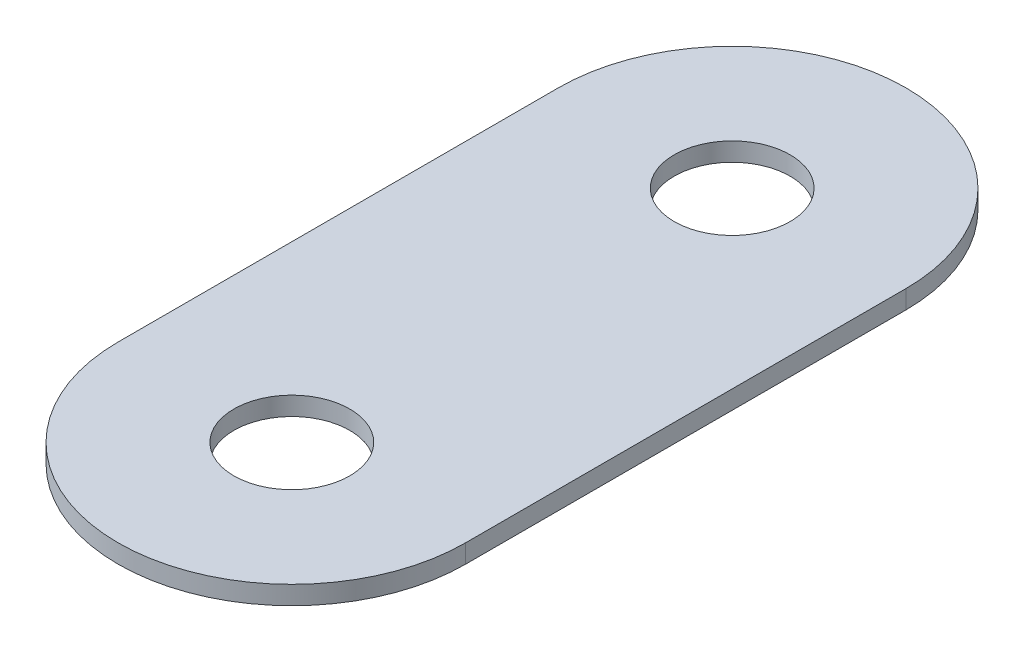
SolidWorks part; units mm, degrees
material "AISI 1020 Steel, Cold Rolled"
ref_plane "Front Plane" through (0, 0, 0) normal (0, 0, 1) x (1, 0, 0)
ref_plane "Top Plane" through (0, 0, 0) normal (0, 1, 0) x (1, 0, 0)
ref_plane "Right Plane" through (0, 0, 0) normal (1, 0, 0) x (0, 0, -1)
sketch "Sketch6" plane through (0, 0, 0) normal (0, 1, 0) x (1, 0, 0)
  line L2 (-15, 19) -> (-15, -19)
  line L4 (15, 19) -> (15, -19)
  arc A0 (15, 19) -> (-15, 19) centre (0, 19) ccw
  arc A1 (-15, -19) -> (15, -19) centre (0, -19) ccw
  point P1 (0, 0)
  point P2 (15, 0)
  dimension "D1" = 15
  dimension "D2" = 38
extrude "Boss-Extrude2" add sketch "Sketch6" along normal mid plane 1.6
sketch "Sketch7" plane through (0, 0, 0) normal (0, 1, 0) x (1, 0, 0)
  circle A0 centre (0, 19) radius 5
  circle A1 centre (0, -19) radius 5
  dimension "D1" = 10
extrude "Cut-Extrude2" cut sketch "Sketch7" against normal through all both and the other way through all
